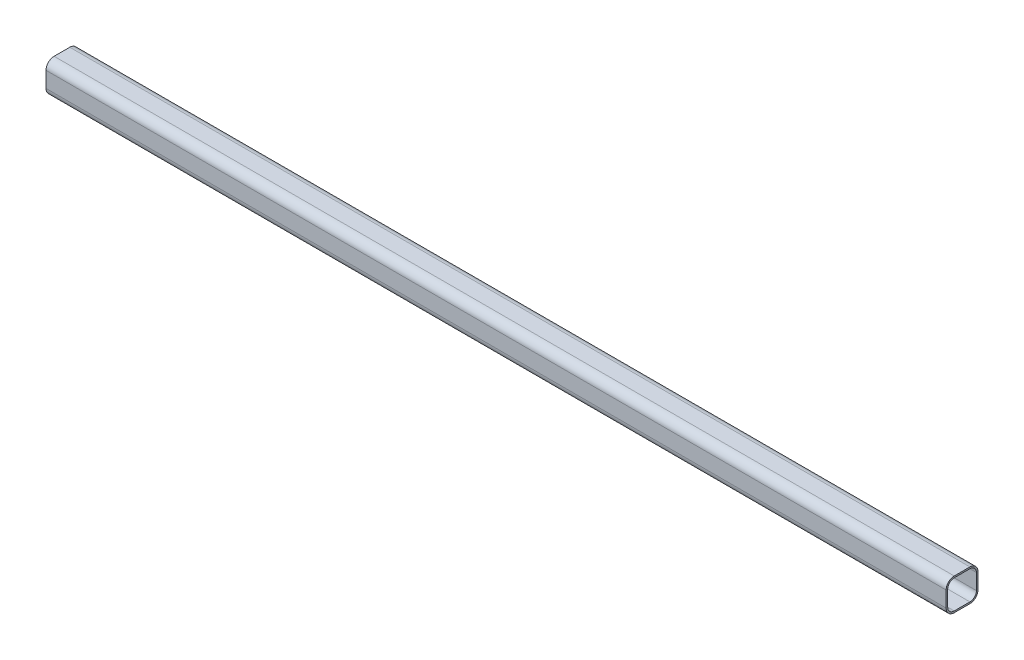
SolidWorks part; units mm, degrees
material "AISI 1015 Acero estirado en frío (SS)"
ref_plane "Alzado" through (0, 0, 0) normal (0, 0, 1) x (1, 0, 0)
ref_plane "Planta" through (0, 0, 0) normal (0, 1, 0) x (1, 0, 0)
ref_plane "Vista lateral" through (0, 0, 0) normal (1, 0, 0) x (0, 0, -1)
sketch "Croquis1" plane through (0, 0, 0) normal (0, 0, 1) x (1, 0, 0)
  line L0 (-623.6352, 0) -> (788.3648, 0)
  dimension "D1" = 1412
other "Miembro estructural1"
ref_plane "Plano1" through (-623.6352, 0, 0) normal (1, 0, 0) x (0, 1, 0)
sketch "Sketch1" plane through (-623.6352, 0, 0) normal (1, 0, 0) x (0, 1, 0)
  line L0 (-12.3, -22.5) -> (12.3, -22.5)
  line L1 (-22.5, -12.3) -> (-22.5, 12.3)
  line L2 (12.3, 22.5) -> (-12.3, 22.5)
  line L3 (22.5, 12.3) -> (22.5, -12.3)
  line L4 (-12.3, -25) -> (12.3, -25)
  line L5 (-25, -12.3) -> (-25, 12.3)
  line L6 (12.3, 25) -> (-12.3, 25)
  line L7 (25, 12.3) -> (25, -12.3)
  line L8 (0, 0) -> (22.5, 0) construction
  line L9 (0, 0) -> (0, 22.5) construction
  arc A0 (25, 12.3) -> (12.3, 25) centre (12.3, 12.3) ccw
  arc A1 (12.3, -25) -> (25, -12.3) centre (12.3, -12.3) ccw
  arc A2 (-25, -12.3) -> (-12.3, -25) centre (-12.3, -12.3) ccw
  arc A3 (-12.3, 25) -> (-25, 12.3) centre (-12.3, 12.3) ccw
  arc A4 (-12.3, 22.5) -> (-22.5, 12.3) centre (-12.3, 12.3) ccw
  arc A5 (22.5, 12.3) -> (12.3, 22.5) centre (12.3, 12.3) ccw
  arc A6 (12.3, -22.5) -> (22.5, -12.3) centre (12.3, -12.3) ccw
  arc A7 (-22.5, -12.3) -> (-12.3, -22.5) centre (-12.3, -12.3) ccw
  point P3 (0, 25)
  point P4 (25, 0)
  point P5 (0, -25)
  point P6 (-25, 0)
  point P7 (-25, 25)
  point P8 (-25, -25)
  point P33 (0, 0)
  point P35 (25, -25)
  point P36 (25, 25)
  point P37 (0, 0)
  dimension "D1" = 12.7
  dimension "Thickness" = 2.5
  dimension "V_leg" = 50
hole_wizard "Taladro de margen para M161" positions "Croquis4" profile "Croquis5" hole size "M16" standard "Ansi Metric"
sketch "Croquis4" plane through (0, -25, 0) normal (0, -1, 0) x (-1, 0, 0)
  line L1 (-82.3648, -25) -> (-82.3648, 25) construction
  line L2 (-788.3648, -25) -> (623.6352, -25) construction
  line L3 (-788.3648, 25) -> (623.6352, 25) construction
  line L7 (-82.3648, 0) -> (-211.5892, 0) construction
  point P0 (-152.3648, 0)
  point P2 (-212.3648, 0)
  dimension "D1" = 70
  dimension "D2" = 130
sketch "Croquis5" plane through (152.3648, -25, 0) normal (1, 0, 0) x (0, 0, -1)
  line L0 (0, 0) -> (0, 2.5)
  line L1 (0, 2.5) -> (8.75, 2.5)
  line L2 (8.75, 2.5) -> (8.75, 0)
  line L5 (8.75, 0) -> (0, 0)
  line L11 (0, -6.35) -> (0, 107.95) construction
  dimension "Diámetro de taladro hasta el siguiente" = 17.5
  dimension "Profundidad de taladro hasta el siguiente" = 2.5
ref_plane "Plano2" through (0, 0, 0) normal (0, 0, 1) x (1, 0, 0)
ref_plane "Plano3" through (82.3648, 0, 0) normal (-1, 0, 0) x (0, 0, 1)
